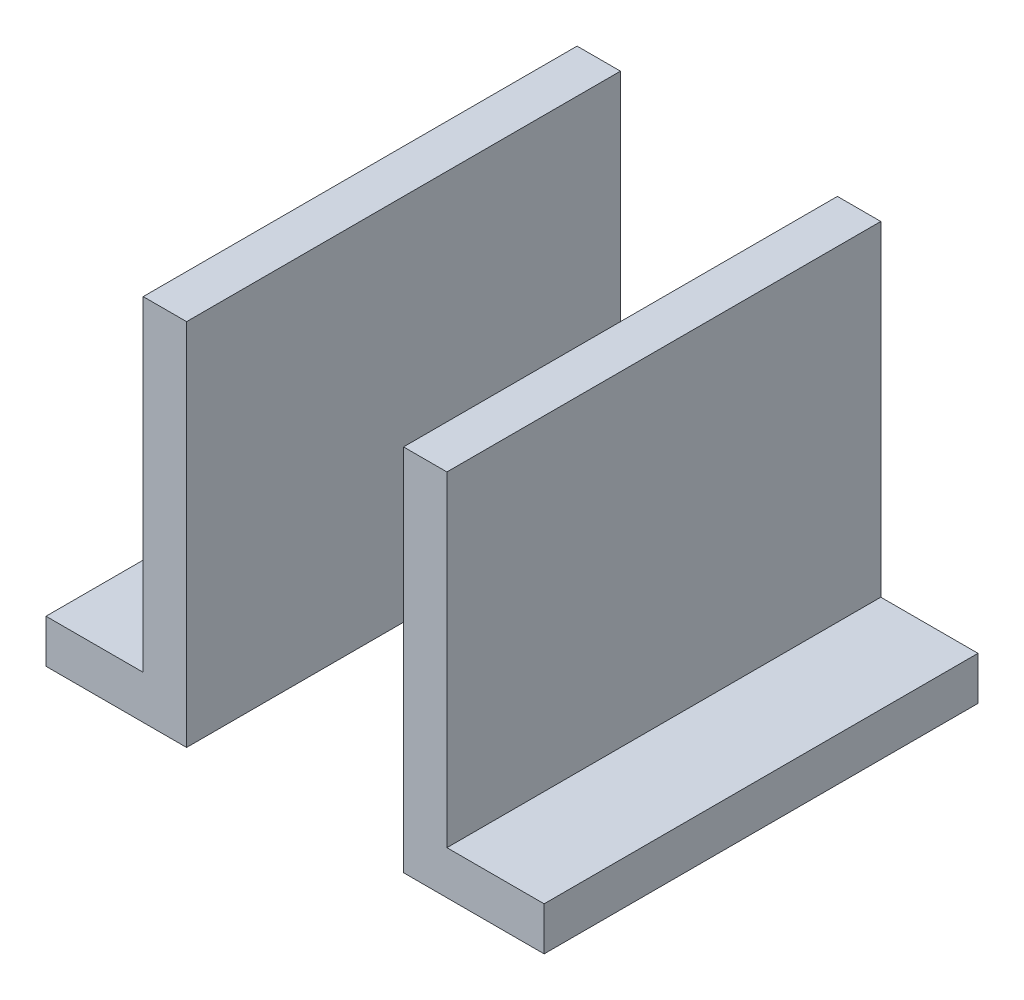
SolidWorks part; units mm, degrees
ref_plane "Front Plane" through (0, 0, 0) normal (0, 0, 1) x (1, 0, 0)
ref_plane "Top Plane" through (0, 0, 0) normal (0, 1, 0) x (1, 0, 0)
ref_plane "Right Plane" through (0, 0, 0) normal (1, 0, 0) x (0, 0, -1)
sketch "Sketch1" plane through (0, 0, 0) normal (0, 0, 1) x (1, 0, 0)
  line L0 (0, 0) -> (0, 22.5728) construction
  line L1 (-57.404, -45.4855) -> (-25, -45.4855)
  line L2 (25, 39.5145) -> (35, 39.5145)
  line L3 (35, 39.5145) -> (35, -35.4855)
  line L4 (35, -35.4855) -> (57.404, -35.4855)
  line L5 (57.404, -35.4855) -> (57.404, -45.4855)
  line L6 (57.404, -45.4855) -> (25, -45.4855)
  line L7 (-57.404, -35.4855) -> (-57.404, -45.4855)
  line L8 (25, 39.5145) -> (25, -45.4855)
  line L9 (-35, -35.4855) -> (-57.404, -35.4855)
  line L10 (-35, 39.5145) -> (-35, -35.4855)
  line L11 (-25, 39.5145) -> (-35, 39.5145)
  line L12 (-25, 39.5145) -> (-25, -45.4855)
  dimension "D1" = 10
  dimension "D2" = 85
  dimension "D3" = 10
  dimension "D4" = 25
extrude "Boss-Extrude1" add sketch "Sketch1" along normal blind 100
